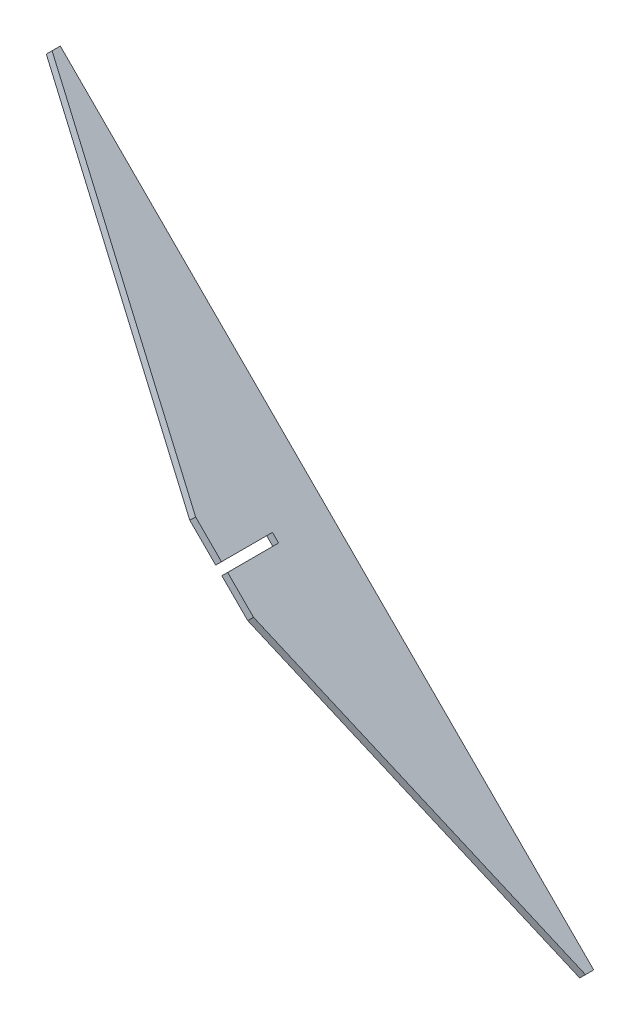
SolidWorks part; units mm, degrees
ref_plane "Front Plane" through (0, 0, 0) normal (0, 0, 1) x (1, 0, 0)
ref_plane "Top Plane" through (0, 0, 0) normal (0, 1, 0) x (1, 0, 0)
ref_plane "Right Plane" through (0, 0, 0) normal (1, 0, 0) x (0, 0, -1)
sketch "Sketch2" plane through (0, 0, 0) normal (0, 0, 1) x (1, 0, 0)
  line L2 (-329, 0) -> (-329, 658) construction
  line L3 (329, 0) -> (329, 658) construction
  line L4 (-329, 658) -> (329, 0) construction
  line L6 (329, 0) -> (329, 7.0711) construction
  line L7 (329, 0) -> (321.9289, 0) construction
  line L9 (321.9289, 0) -> (329, 7.0711)
  line L10 (-329, 0) -> (329, 658) construction
  line L11 (-329, 650.9289) -> (-321.9289, 658)
  line L12 (-329, 650.9289) -> (321.9289, 0)
  line L13 (329, 7.0711) -> (-321.9289, 658)
  dimension "D1" = 10
  dimension "D2" = 90
  dimension "D3" = 45
  dimension "D4" = 45
  dimension "D5" = 920.5525
extrude "Boss-Extrude1" add sketch "Sketch2" along normal offset from surface 125 and the other way up to surface (10 mm away)
ref_plane "Plane1" through (160.9645, 160.9645, 0) normal (-0.7071, -0.7071, 0) x (-0.7071, 0.7071, 0)
sketch "Sketch3" plane through (160.9645, 160.9645, 0) normal (-0.7071, -0.7071, 0) x (-0.7071, 0.7071, 0)
  line L0 (232.6381, -250) -> (232.6381, 10) construction
  line L1 (282.6381, -115) -> (182.6381, -115) construction
  line L2 (692.9144, 10) -> (-227.6381, 10) construction
  line L3 (692.9144, 0) -> (282.6381, -115)
  line L4 (692.9144, 10) -> (-227.6381, 10)
  line L5 (-227.6381, 10) -> (-227.6381, -115)
  line L6 (-227.6381, -115) -> (692.9144, -115)
  line L7 (692.9144, -115) -> (692.9144, 10)
  line L8 (232.6381, 10) -> (-227.6381, 10)
  line L9 (-227.6381, 10) -> (-227.6381, -115)
  line L11 (692.9144, -115) -> (692.9144, 0)
  line L12 (692.9144, -115) -> (282.6381, -115)
  line L13 (-227.6381, 0) -> (182.6381, -115)
  line L14 (-227.6381, -115) -> (-227.6381, 0)
  line L15 (-227.6381, -115) -> (182.6381, -115)
  point P9 (232.6381, -115)
  dimension "D2" = 50
  dimension "D3" = 10
  dimension "D1" = 0
extrude "Cut-Extrude1" cut sketch "Sketch3" against normal blind 10 contours L9 L15 L13 | L12 L11 L3
sketch "Sketch4" plane through (160.9645, 160.9645, 0) normal (-0.7071, -0.7071, 0) x (-0.7071, 0.7071, 0)
  line L0 (-227.6381, 10) -> (692.9144, 10) construction
  line L1 (237.9381, -52.8) -> (227.3381, -52.8)
  line L10 (282.6381, -115) -> (182.6381, -115) construction
  line L11 (-227.6381, 10) -> (692.9144, 10) construction
  line L12 (282.6381, -115) -> (182.6381, -115) construction
  line L13 (232.6381, -115) -> (232.6381, 10) construction
  line L14 (227.3381, -115) -> (237.9381, -115)
  line L15 (237.9381, -115) -> (237.9381, -52.8)
  line L16 (227.3381, -115) -> (227.3381, -52.8)
  point P9 (232.6381, -52.8)
  point P12 (232.6381, -115)
  dimension "D1" = 10.6
  dimension "D2" = 62.2
extrude "Cut-Extrude2" cut sketch "Sketch4" against normal through all
sketch "Sketch5" plane through (0, 0, -10) normal (0, 0, -1) x (-1, 0, 0)
  line L0 (-3.5355, 332.5355) -> (3.5355, 325.4645) construction
  line L4 (-321.9289, 0) -> (329, 650.9289)
  line L5 (329, 650.9289) -> (321.9289, 658)
  line L6 (321.9289, 658) -> (-329, 7.0711)
  line L7 (-329, 7.0711) -> (-321.9289, 0)
  line L8 (-321.9289, 0) -> (329, 650.9289) construction
  line L9 (329, 650.9289) -> (321.9289, 658) construction
  line L10 (321.9289, 658) -> (-329, 7.0711) construction
  line L11 (-329, 7.0711) -> (-321.9289, 0) construction
  circle A0 centre (0, 329) radius 17.9481
  dimension "D1" = 0
ref_plane "Plane2" through (164.5, 164.5, 0) normal (-0.7071, -0.7071, 0) x (-0.7071, 0.7071, 0)
